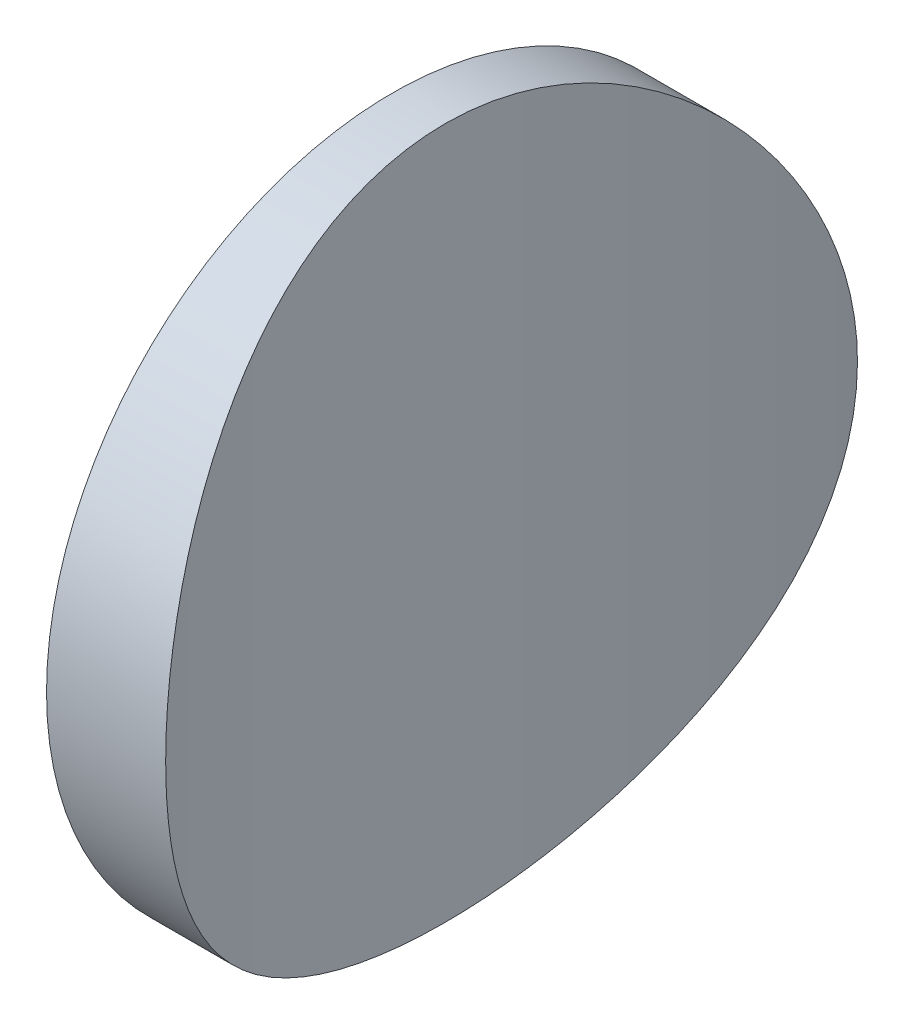
SolidWorks part; units mm, degrees
ref_plane "Спереди" through (0, 0, 0) normal (0, 0, 1) x (1, 0, 0)
ref_plane "Сверху" through (0, 0, 0) normal (0, 1, 0) x (1, 0, 0)
ref_plane "Справа" through (0, 0, 0) normal (1, 0, 0) x (0, 0, -1)
sketch "Эскиз1" plane through (0, 0, 0) normal (1, 0, 0) x (0, 0, -1)
  circle A0 centre (0, 0) radius 85
  dimension "D1" = 170
extrude "Бобышка-Вытянуть1" add sketch "Эскиз1" along normal blind 50
sketch "Эскиз2" plane through (0, 0, 0) normal (0, 1, 0) x (1, 0, 0)
  line L0 (13, 66.1796) -> (13, -65.5965) construction
  line L1 (0, 85) -> (0, -85) construction
  circle A0 centre (243, 0) radius 230
  dimension "D2" = 460
  dimension "D1" = 13
extrude "Вырез-Вытянуть1" cut sketch "Эскиз2" against normal through all and the other way through all
